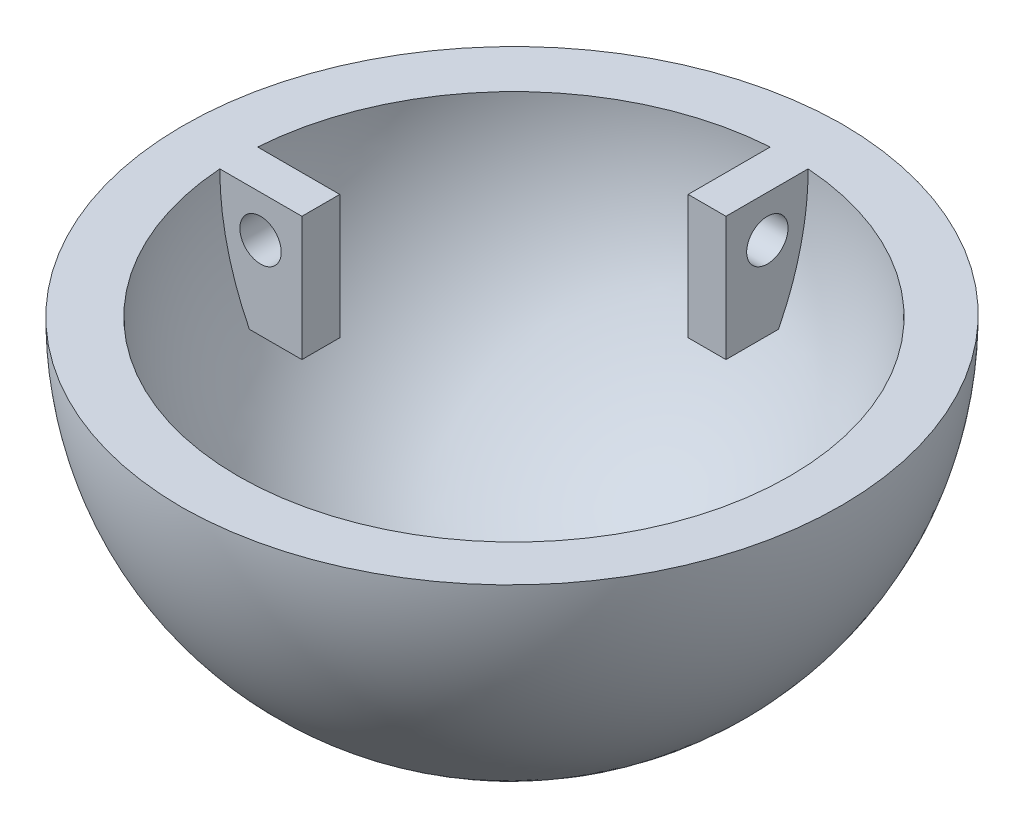
SolidWorks part; units mm, degrees
ref_plane "Front Plane" through (0, 0, 0) normal (0, 0, 1) x (1, 0, 0)
ref_plane "Top Plane" through (0, 0, 0) normal (0, 1, 0) x (1, 0, 0)
ref_plane "Right Plane" through (0, 0, 0) normal (1, 0, 0) x (0, 0, -1)
sketch "Sketch1" plane through (0, 0, 0) normal (0, 1, 0) x (1, 0, 0)
  line L0 (-0.1402, 11.9992) -> (0, -12)
  arc A0 (-0.1402, 11.9992) -> (0, -12) centre (0, 0) ccw
  dimension "D1" = 12
revolve "Revolve1" add sketch "Sketch1" angle 180 about L0
sketch "Sketch2" plane through (0, 0, 0) normal (0, 1, 0) x (1, 0, 0)
  line L0 (0, -10) -> (0, 10)
  arc A0 (0, 10) -> (0, -10) centre (0, 0) ccw
  arc A1 (-0.1402, 11.9992) -> (0, -12) centre (0, 0) ccw construction
  dimension "D1" = 2
revolve "Cut-Revolve1" cut sketch "Sketch2" angle 360 about L0
sketch "Sketch3" plane through (0, 0, 0) normal (0, 1, 0) x (1, 0, 0)
  line L0 (-0.6859, 10.9998) -> (0.6859, 10.9998)
  line L1 (-10.9998, -0.6859) -> (-6.9998, -0.6859)
  line L2 (-10.9998, -0.6859) -> (-10.9998, 0.6859)
  line L3 (-10.9998, 0.6859) -> (-6.9998, 0.6859)
  line L4 (-6.9998, -0.6859) -> (-6.9998, 0.6859)
  line L5 (-0.6859, 10.9998) -> (-0.6859, 6.9998)
  line L6 (-0.6859, 6.9998) -> (0.6859, 6.9998)
  line L7 (0.6859, 10.9998) -> (0.6859, 6.9998)
  arc A0 (-0.1402, 11.9992) -> (0, -12) centre (0, 0) ccw construction
  point P4 (-6.9998, 0)
  point P9 (-11.9998, -0.0701)
  point P17 (0, 0)
  dimension "D1" = 0
  dimension "D2" = 1
  dimension "D3" = 4
  dimension "D4" = 2
extrude "Boss-Extrude1" add sketch "Sketch3" against normal blind 4.5
sketch "Sketch4" plane through (0, 0, -0.6859) normal (0, 0, -1) x (-1, 0, 0)
  line L0 (6.9998, 0) -> (9.9765, 0) construction
  line L1 (6.9998, -4.5) -> (6.9998, 0) construction
  circle A0 centre (8.4998, -1.5) radius 0.75
  dimension "D1" = 1.5
  dimension "D2" = 1.5
  dimension "D3" = 1.5
extrude "Cut-Extrude1" cut sketch "Sketch4" against normal up to next
sketch "Sketch5" plane through (0.6859, 0, 0) normal (1, 0, 0) x (0, 0, -1)
  line L0 (6.9998, 0) -> (9.9765, 0) construction
  line L1 (6.9998, -4.5) -> (6.9998, 0) construction
  circle A0 centre (8.4998, -1.5) radius 0.75
  dimension "D1" = 1.5
  dimension "D3" = 1.5
  dimension "D2" = 1.5
extrude "Cut-Extrude2" cut sketch "Sketch5" against normal up to next
